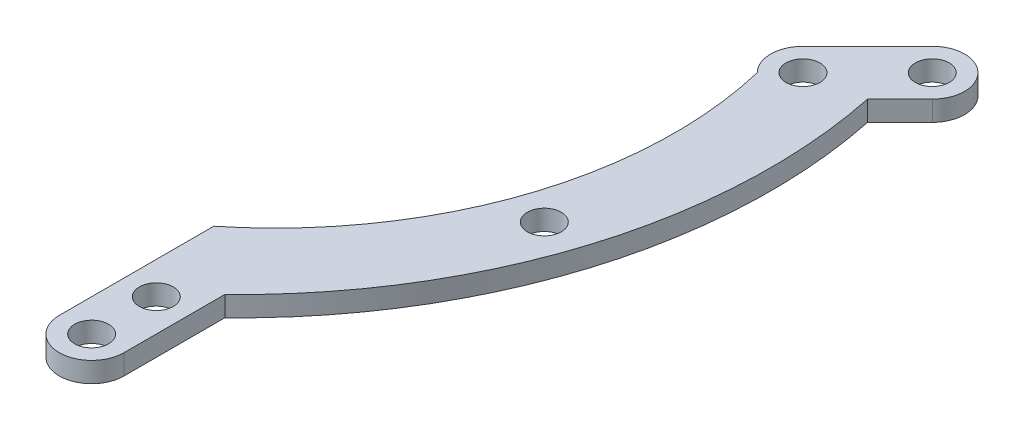
SolidWorks part; units mm, degrees
ref_plane "Front" through (0, 0, 0) normal (0, 0, 1) x (1, 0, 0)
ref_plane "Top" through (0, 0, 0) normal (0, 1, 0) x (1, 0, 0)
ref_plane "Right" through (0, 0, 0) normal (1, 0, 0) x (0, 0, -1)
sketch "Sketch1" plane through (0, 0, 0) normal (0, 1, 0) x (1, 0, 0)
  line L1 (4, -36) -> (4, -40)
  line L2 (-4, -32) -> (-4, -40)
  line L3 (16, 32) -> (24, 40) construction
  line L4 (13.1716, 34.8284) -> (21.1716, 42.8284)
  line L5 (22.8284, 33.1716) -> (26.8284, 37.1716)
  line L10 (0, -37.9) -> (0, -40) construction
  line L11 (-4, -20.8947) -> (-4, -32)
  line L12 (4, -27.5251) -> (4, -36)
  circle A0 centre (0, -32) radius 2.1
  circle A1 centre (0, -40) radius 2.1
  circle A2 centre (16, 32) radius 2.1
  circle A3 centre (24, 40) radius 2.1
  arc A5 (-4, -40) -> (4, -40) centre (0, -40) ccw
  arc A7 (26.8284, 37.1716) -> (21.1716, 42.8284) centre (24, 40) ccw
  arc A11 (13.1716, 34.8284) -> (13.1716, 29.1716) centre (16, 32) ccw
  arc A12 (4, -27.5251) -> (22.8284, 33.1716) centre (-41.5781, 19.8821) ccw
  arc A13 (-4, -20.8947) -> (13.1716, 29.1716) centre (-34.9553, 17.7001) ccw
  circle A14 centre (16, 0) radius 2.1
  point P1 (0, -4)
  point P14 (20, 36)
extrude "Boss-Extrude1" add sketch "Sketch1" along normal blind 2.5
